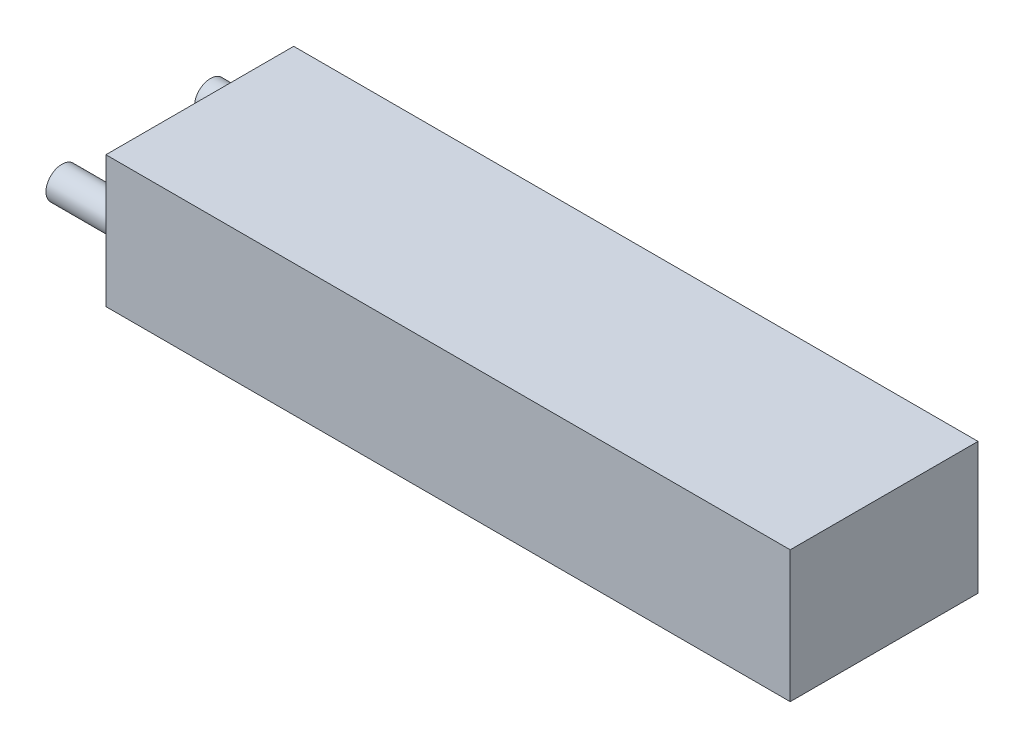
SolidWorks part; units mm, degrees
ref_plane "Front Plane" through (0, 0, 0) normal (0, 0, 1) x (1, 0, 0)
ref_plane "Top Plane" through (0, 0, 0) normal (0, 1, 0) x (1, 0, 0)
ref_plane "Right Plane" through (0, 0, 0) normal (1, 0, 0) x (0, 0, -1)
sketch "Sketch1" plane through (0, 0, 0) normal (0, 1, 0) x (1, 0, 0)
  line L1 (-32.25, 8.85) -> (32.25, 8.85)
  line L2 (-32.25, 8.85) -> (-32.25, -8.85)
  line L3 (-32.25, -8.85) -> (32.25, -8.85)
  line L4 (32.25, 8.85) -> (32.25, -8.85)
  line L5 (-32.25, 8.85) -> (32.25, -8.85) construction
  line L6 (-32.25, -8.85) -> (32.25, 8.85) construction
  point P0 (0, 0)
  dimension "D1" = 17.7
  dimension "D2" = 64.5
extrude "Boss-Extrude1" add sketch "Sketch1" along normal mid plane 12.4
sketch "Sketch2" plane through (-32.25, 0, 0) normal (-1, 0, 0) x (0, 0, 1)
  line L0 (0, 6.2) -> (0, -6.2) construction
  line L1 (-8.85, 6.2) -> (8.85, 6.2) construction
  line L2 (-8.85, -6.2) -> (8.85, -6.2) construction
  circle A0 centre (-7, 0) radius 1.5
  circle A1 centre (7, 0) radius 1.5
  point P8 (0, 0)
  point P10 (-6.8134, 0)
  dimension "D1" = 3
  dimension "D2" = 7
extrude "Boss-Extrude2" add sketch "Sketch2" along normal mid plane 12
